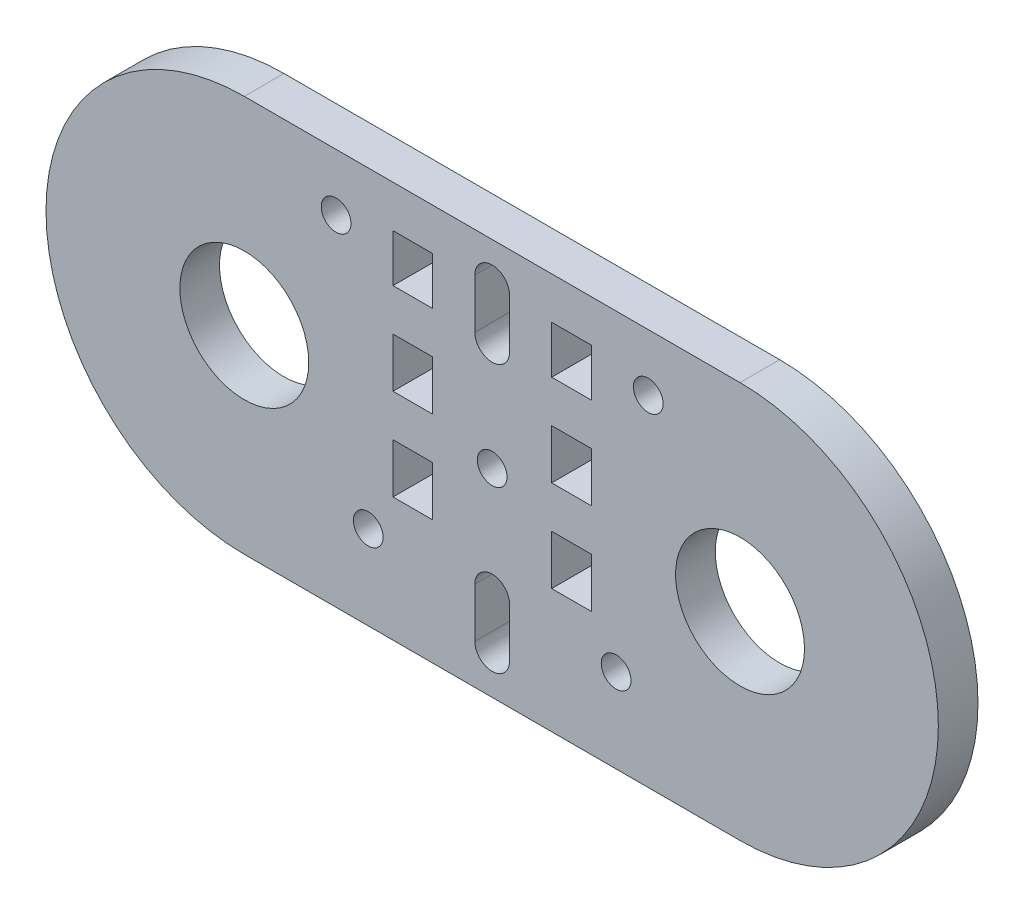
SolidWorks part; units mm, degrees
ref_plane "前视基准面" through (0, 0, 0) normal (0, 0, 1) x (1, 0, 0)
ref_plane "上视基准面" through (0, 0, 0) normal (0, 1, 0) x (1, 0, 0)
ref_plane "右视基准面" through (0, 0, 0) normal (1, 0, 0) x (0, 0, -1)
sketch "草图1" plane through (0, 0, 0) normal (0, 0, 1) x (1, 0, 0)
  line L0 (-11.3774, 24.1048) -> (38.6226, 24.1048) construction
  line L1 (13.6226, 24.1048) -> (13.6226, 7.3546) construction
  line L2 (-11.3774, 44.1048) -> (9.6226, 44.1048)
  line L3 (-11.3774, 4.1048) -> (38.6226, 4.1048)
  line L4 (1.1226, 24.1048) -> (1.1226, 12.583) construction
  line L5 (17.6226, 44.1048) -> (9.6226, 44.1048)
  line L6 (23.6226, 35.0748) -> (19.6226, 35.0748)
  line L7 (23.6226, 25.8448) -> (19.6226, 25.8448)
  line L8 (7.6226, 39.8748) -> (7.6226, 35.0748)
  line L9 (3.6226, 39.8748) -> (7.6226, 39.8748)
  line L10 (3.6226, 35.0748) -> (3.6226, 39.8748)
  line L11 (3.6226, 30.8448) -> (7.6226, 30.8448)
  line L12 (3.6226, 25.8448) -> (3.6226, 30.8448)
  line L13 (7.6226, 30.8448) -> (7.6226, 25.8448)
  line L14 (7.6226, 21.6148) -> (7.6226, 16.6148)
  line L15 (3.6226, 16.6148) -> (3.6226, 21.6148)
  line L16 (7.6226, 16.6148) -> (3.6226, 16.6148)
  line L17 (3.6226, 21.6148) -> (7.6226, 21.6148)
  line L18 (3.6226, 25.8448) -> (7.6226, 25.8448)
  line L19 (3.6226, 35.0748) -> (7.6226, 35.0748)
  line L20 (23.6226, 21.6148) -> (19.6226, 21.6148)
  line L21 (19.6226, 16.6148) -> (23.6226, 16.6148)
  line L22 (23.6226, 16.6148) -> (23.6226, 21.6148)
  line L23 (19.6226, 21.6148) -> (19.6226, 16.6148)
  line L24 (19.6226, 30.8448) -> (19.6226, 25.8448)
  line L25 (23.6226, 25.8448) -> (23.6226, 30.8448)
  line L26 (23.6226, 30.8448) -> (19.6226, 30.8448)
  line L27 (23.6226, 35.0748) -> (23.6226, 39.8748)
  line L28 (23.6226, 39.8748) -> (19.6226, 39.8748)
  line L29 (19.6226, 39.8748) -> (19.6226, 35.0748)
  line L36 (17.6226, 44.1048) -> (38.6226, 44.1048)
  line L37 (11.8726, 8.1271) -> (11.8726, 13.1271)
  line L38 (15.3726, 8.1271) -> (15.3726, 13.1271)
  line L39 (15.3726, 40.1271) -> (15.3726, 35.1271)
  line L40 (11.8726, 40.1271) -> (11.8726, 35.1271)
  circle A0 centre (-11.3774, 24.1048) radius 12.5 construction
  circle A1 centre (1.1226, 12.583) radius 1.5
  circle A2 centre (26.1226, 12.583) radius 1.5
  circle A4 centre (13.6226, 24.1048) radius 1.5
  circle A8 centre (-11.3774, 24.1048) radius 6.5
  circle A9 centre (38.6226, 24.1048) radius 6.5
  circle A10 centre (38.6226, 24.1048) radius 17 construction
  circle A11 centre (29.3636, 38.3621) radius 1.5
  arc A13 (15.3726, 13.1271) -> (11.8726, 13.1271) centre (13.6226, 13.1271) ccw
  arc A14 (11.8726, 8.1271) -> (15.3726, 8.1271) centre (13.6226, 8.1271) ccw
  circle A15 centre (-11.3774, 24.1048) radius 17 construction
  circle A16 centre (-2.1184, 38.3621) radius 1.5
  arc A17 (11.8726, 40.1271) -> (15.3726, 40.1271) centre (13.6226, 40.1271) cw
  arc A18 (-11.3774, 44.1048) -> (-11.3774, 4.1048) centre (-11.3774, 24.1048) ccw
  arc A19 (38.6226, 4.1048) -> (38.6226, 44.1048) centre (38.6226, 24.1048) ccw
  arc A20 (15.3726, 35.1271) -> (11.8726, 35.1271) centre (13.6226, 35.1271) cw
  point P15 (-11.3774, 24.1048)
  point P17 (13.6226, 24.1048)
  point P23 (13.6226, 24.1048)
  point P26 (38.6226, 24.1048)
  point P43 (13.6226, 24.1048)
  point P56 (13.6226, 24.1048)
  point P58 (13.6226, 27.3769)
  point P77 (13.6226, 24.1048)
  point P78 (13.6226, 12.0848)
  point P79 (13.6226, 24.1048)
  point P80 (13.6226, 12.0848)
  point P81 (13.6226, 27.3769)
  point P82 (13.6226, 20.8549)
  point P83 (13.6226, 8.8349)
  point P84 (13.6226, 20.8549)
  point P85 (13.6226, 8.8349)
  point P86 (13.6226, 24.1271)
  dimension "D1" = 50
extrude "凸台-拉伸1" add sketch "草图1" along normal blind 4
